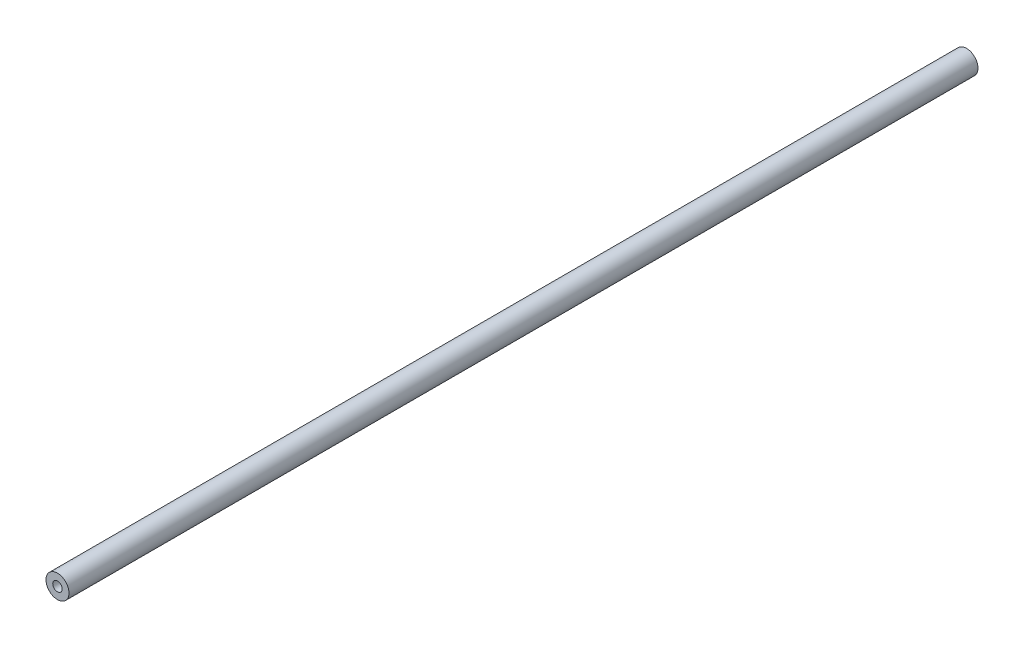
SolidWorks part; units mm, degrees
material "Латунь"
ref_plane "Спереди" through (0, 0, 0) normal (0, 0, 1) x (1, 0, 0)
ref_plane "Сверху" through (0, 0, 0) normal (0, 1, 0) x (1, 0, 0)
ref_plane "Справа" through (0, 0, 0) normal (1, 0, 0) x (0, 0, -1)
other "Configuration Table"
sketch "Эскиз1" plane through (0, 0, 0) normal (0, 0, 1) x (1, 0, 0)
  line L0 (235.7213, -388.4131) -> (236.321, -388.4131) construction
  circle A0 centre (0, 0) radius 4
  dimension "D1" = 8
extrude "Бобышка-Вытянуть1" add sketch "Эскиз1" along normal mid plane 316
sketch "Эскиз2" plane through (0, 0, 158) normal (0, 0, 1) x (1, 0, 0)
  circle A0 centre (0, 0) radius 1.25
  dimension "D1" = 2.5
sketch "Эскиз3" plane through (0, 0, -158) normal (0, 0, -1) x (-1, 0, 0)
  circle A0 centre (0, 0) radius 1.25
  dimension "D1" = 2.5
hole_wizard "Отверстие обработанное метчиком M4x0.72" positions "Эскиз4" profile "Эскиз5" tap size "M4x0.7" standard "Ansi Metric"
sketch "Эскиз4" plane through (0, 0, -158) normal (0, 0, -1) x (-1, 0, 0)
  point P0 (0, 0)
sketch "Эскиз5" plane through (0, 0, -158) normal (1, 0, 0) x (0, 1, 0)
  line L0 (0, 0) -> (0, 19.9914)
  line L1 (0, 19.9914) -> (1.65, 19)
  line L2 (1.65, 19) -> (1.65, 0)
  line L5 (1.65, 0) -> (0, 0)
  line L10 (0, 19.9914) -> (-1.65, 19) construction
  line L11 (0, -6.35) -> (0, 107.95) construction
  dimension "Диаметр сверла" = 3.3
  dimension "Глубина сверла" = 19
  dimension "Угол заточки сверла" = 118
hole_wizard "Отверстие обработанное метчиком M4x0.71" positions "Эскиз6" profile "Эскиз7" tap size "M4x0.7" standard "Ansi Metric"
sketch "Эскиз6" plane through (0, 0, 158) normal (0, 0, 1) x (1, 0, 0)
  point P0 (0, 0)
sketch "Эскиз7" plane through (0, 0, 158) normal (1, 0, 0) x (0, -1, 0)
  line L0 (0, 0) -> (0, 19.9914)
  line L1 (0, 19.9914) -> (1.65, 19)
  line L2 (1.65, 19) -> (1.65, 0)
  line L5 (1.65, 0) -> (0, 0)
  line L10 (0, 19.9914) -> (-1.65, 19) construction
  line L11 (0, -6.35) -> (0, 107.95) construction
  dimension "Диаметр сверла" = 3.3
  dimension "Глубина сверла" = 19
  dimension "Угол заточки сверла" = 118
sketch "Эскиз13" plane through (0, 0, 158) normal (0, 0, 1) x (1, 0, 0)
  line L0 (4, 0) -> (-4, 0) construction
  line L1 (0, 4) -> (0, -4) construction
  circle A0 centre (0, 0) radius 4 construction
